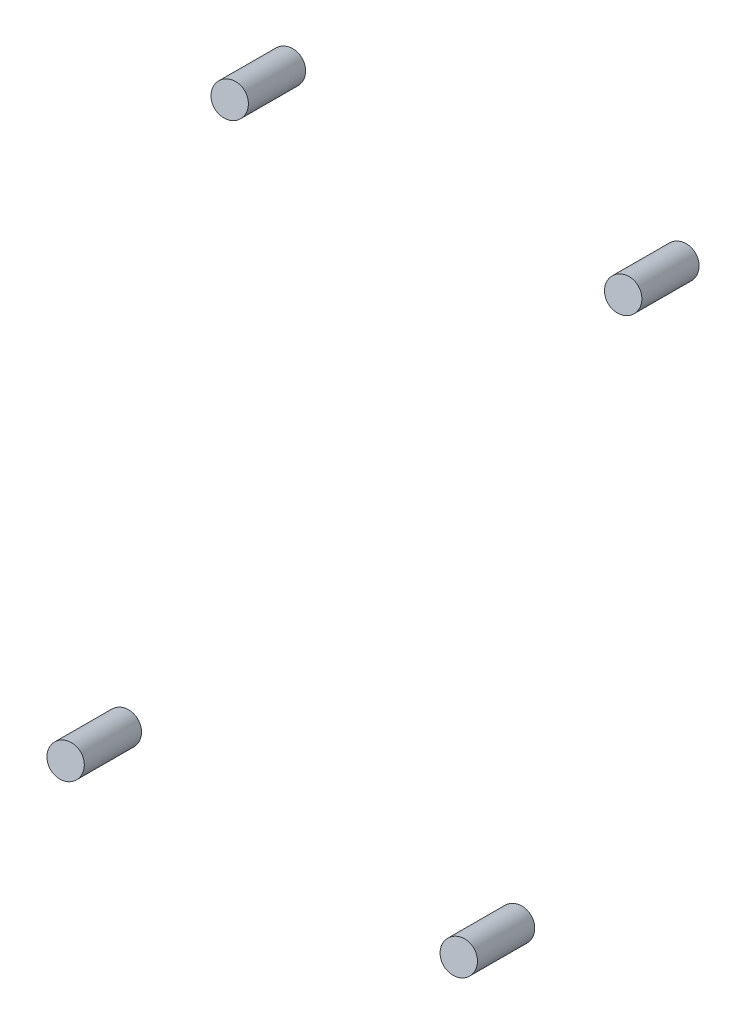
SolidWorks part; units mm, degrees
ref_plane "Front Plane" through (0, 0, 0) normal (0, 0, 1) x (1, 0, 0)
ref_plane "Top Plane" through (0, 0, 0) normal (0, 1, 0) x (1, 0, 0)
ref_plane "Right Plane" through (0, 0, 0) normal (1, 0, 0) x (0, 0, -1)
sketch "Sketch1" plane through (-87.6708, -88.3464, -389.5162) normal (0.2144, 0.216, 0.9526) x (0.9767, -0.0474, -0.2091)
  circle A0 centre (229.7115, 309.2332) radius 2
  circle A1 centre (273.0519, 306.3807) radius 2
  circle A3 centre (224.903, 239.2943) radius 2
  circle A4 centre (268.2347, 236.3151) radius 2
  dimension "D1" = 4
  dimension "D2" = 4
  dimension "D3" = 4
  dimension "D4" = 4
extrude "Boss-Extrude1" add sketch "Sketch1" along normal blind 10
